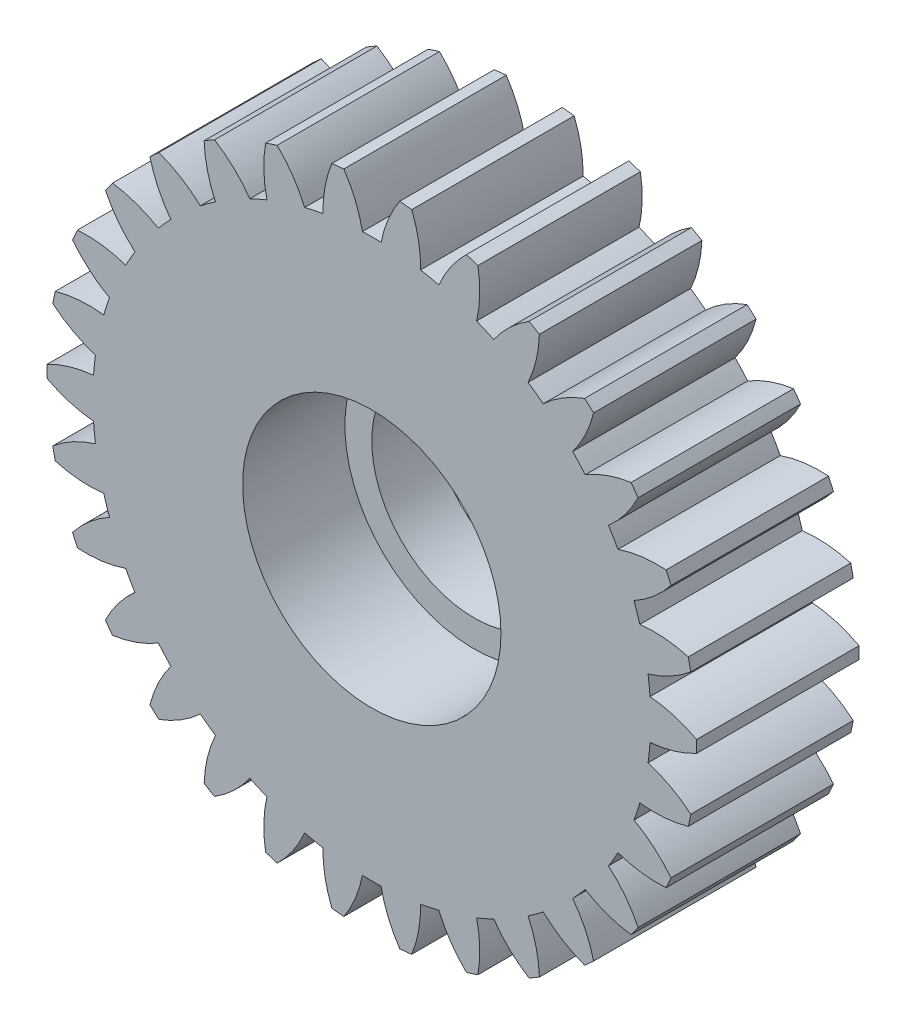
SolidWorks part; units mm, degrees
ref_plane "Front Plane" through (0, 0, 0) normal (0, 0, 1) x (1, 0, 0)
ref_plane "Top Plane" through (0, 0, 0) normal (0, 1, 0) x (1, 0, 0)
ref_plane "Right Plane" through (0, 0, 0) normal (1, 0, 0) x (0, 0, -1)
sketch "Sketch1" plane through (0, 0, 0) normal (0, 0, 1) x (1, 0, 0)
  arc B0 (-12.6978, -0.2355) -> (-10.8753, -0.7756) centre (-10.4606, 3.9688) ccw
  arc B1 (-10.8753, -0.7756) -> (-10.7989, -1.5025) centre (0, 0) ccw
  arc B2 (-10.7989, -1.5025) -> (-12.4693, -2.4097) centre (-9.4069, -6.057) ccw
  arc B3 (-12.4693, -2.4097) -> (-12.3714, -2.8704) centre (0, 0) ccw
  arc B4 (-12.3714, -2.8704) -> (-10.4764, -3.0197) centre (-11.0572, 1.7072) ccw
  arc B5 (-10.4764, -3.0197) -> (-10.2506, -3.7149) centre (0, 0) ccw
  arc B6 (-10.2506, -3.7149) -> (-11.6958, -4.9495) centre (-7.942, -7.8804) ccw
  arc B7 (-11.6958, -4.9495) -> (-11.5042, -5.3798) centre (0, 0) ccw
  arc B8 (-11.5042, -5.3798) -> (-9.6197, -5.1319) centre (-11.1705, -0.629) ccw
  arc B9 (-9.6197, -5.1319) -> (-9.2542, -5.7649) centre (0, 0) ccw
  arc B10 (-9.2542, -5.7649) -> (-10.4112, -7.2731) centre (-6.13, -9.3594) ccw
  arc B11 (-10.4112, -7.2731) -> (-10.1343, -7.6541) centre (0, 0) ccw
  arc B12 (-10.1343, -7.6541) -> (-8.3425, -7.0198) centre (-10.7956, -2.9377) ccw
  arc B13 (-8.3425, -7.0198) -> (-7.8534, -7.563) centre (0, 0) ccw
  arc B14 (-7.8534, -7.563) -> (-8.6715, -9.2787) centre (-4.0501, -10.4294) ccw
  arc B15 (-8.6715, -9.2787) -> (-8.3215, -9.5939) centre (0, 0) ccw
  arc B16 (-8.3215, -9.5939) -> (-6.7006, -8.6009) centre (-9.9489, -5.1181) ccw
  arc B17 (-6.7006, -8.6009) -> (-6.1093, -9.0305) centre (0, 0) ccw
  arc B18 (-6.1093, -9.0305) -> (-6.5529, -10.8789) centre (-1.7932, -11.0436) ccw
  arc B19 (-6.5529, -10.8789) -> (-6.145, -11.1144) centre (0, 0) ccw
  arc B20 (-6.145, -11.1144) -> (-4.766, -9.8061) centre (-8.6674, -7.0747) ccw
  arc B21 (-4.766, -9.8061) -> (-4.0983, -10.1034) centre (0, 0) ccw
  arc B22 (-4.0983, -10.1034) -> (-4.1478, -12.0036) centre (0.5421, -11.1751) ccw
  arc B23 (-4.1478, -12.0036) -> (-3.6999, -12.1491) centre (0, 0) ccw
  arc B24 (-3.6999, -12.1491) -> (-2.623, -10.5827) centre (-7.0071, -8.7222) ccw
  arc B25 (-2.623, -10.5827) -> (-1.9081, -10.7347) centre (0, 0) ccw
  arc B26 (-1.9081, -10.7347) -> (-1.5615, -12.6036) centre (2.8537, -10.8182) ccw
  arc B27 (-1.5615, -12.6036) -> (-1.0931, -12.6529) centre (0, 0) ccw
  arc B28 (-1.0931, -12.6529) -> (-0.3654, -10.8968) centre (-5.0405, -9.9885) ccw
  arc B29 (-0.3654, -10.8968) -> (0.3654, -10.8968) centre (0, 0) ccw
  arc B30 (0.3654, -10.8968) -> (1.0931, -12.6529) centre (5.0405, -9.9885) ccw
  arc B31 (1.0931, -12.6529) -> (1.5615, -12.6036) centre (0, 0) ccw
  arc B32 (1.5615, -12.6036) -> (1.9081, -10.7347) centre (-2.8537, -10.8182) ccw
  arc B33 (1.9081, -10.7347) -> (2.623, -10.5827) centre (0, 0) ccw
  arc B34 (2.623, -10.5827) -> (3.6999, -12.1491) centre (7.0071, -8.7222) ccw
  arc B35 (3.6999, -12.1491) -> (4.1478, -12.0036) centre (0, 0) ccw
  arc B36 (4.1478, -12.0036) -> (4.0983, -10.1034) centre (-0.5421, -11.1751) ccw
  arc B37 (4.0983, -10.1034) -> (4.766, -9.8061) centre (0, 0) ccw
  arc B38 (4.766, -9.8061) -> (6.145, -11.1144) centre (8.6674, -7.0747) ccw
  arc B39 (6.145, -11.1144) -> (6.5529, -10.8789) centre (0, 0) ccw
  arc B40 (6.5529, -10.8789) -> (6.1093, -9.0305) centre (1.7932, -11.0436) ccw
  arc B41 (6.1093, -9.0305) -> (6.7006, -8.6009) centre (0, 0) ccw
  arc B42 (6.7006, -8.6009) -> (8.3215, -9.5939) centre (9.9489, -5.1181) ccw
  arc B43 (8.3215, -9.5939) -> (8.6715, -9.2787) centre (0, 0) ccw
  arc B44 (8.6715, -9.2787) -> (7.8534, -7.563) centre (4.0501, -10.4294) ccw
  arc B45 (7.8534, -7.563) -> (8.3425, -7.0198) centre (0, 0) ccw
  arc B46 (8.3425, -7.0198) -> (10.1343, -7.6541) centre (10.7956, -2.9377) ccw
  arc B47 (10.1343, -7.6541) -> (10.4112, -7.2731) centre (0, 0) ccw
  arc B48 (10.4112, -7.2731) -> (9.2542, -5.7649) centre (6.13, -9.3594) ccw
  arc B49 (9.2542, -5.7649) -> (9.6197, -5.1319) centre (0, 0) ccw
  arc B50 (9.6197, -5.1319) -> (11.5042, -5.3798) centre (11.1705, -0.629) ccw
  arc B51 (11.5042, -5.3798) -> (11.6958, -4.9495) centre (0, 0) ccw
  arc B52 (11.6958, -4.9495) -> (10.2506, -3.7149) centre (7.942, -7.8804) ccw
  arc B53 (10.2506, -3.7149) -> (10.4764, -3.0197) centre (0, 0) ccw
  arc B54 (10.4764, -3.0197) -> (12.3714, -2.8704) centre (11.0572, 1.7072) ccw
  arc B55 (12.3714, -2.8704) -> (12.4693, -2.4097) centre (0, 0) ccw
  arc B56 (12.4693, -2.4097) -> (10.7989, -1.5025) centre (9.4069, -6.057) ccw
  arc B57 (10.7989, -1.5025) -> (10.8753, -0.7756) centre (0, 0) ccw
  arc B58 (10.8753, -0.7756) -> (12.6978, -0.2355) centre (10.4606, 3.9688) ccw
  arc B59 (12.6978, -0.2355) -> (12.6978, 0.2355) centre (0, 0) ccw
  arc B60 (12.6978, 0.2355) -> (10.8753, 0.7756) centre (10.4606, -3.9688) ccw
  arc B61 (10.8753, 0.7756) -> (10.7989, 1.5025) centre (0, 0) ccw
  arc B62 (10.7989, 1.5025) -> (12.4693, 2.4097) centre (9.4069, 6.057) ccw
  arc B63 (12.4693, 2.4097) -> (12.3714, 2.8704) centre (0, 0) ccw
  arc B64 (12.3714, 2.8704) -> (10.4764, 3.0197) centre (11.0572, -1.7072) ccw
  arc B65 (10.4764, 3.0197) -> (10.2506, 3.7149) centre (0, 0) ccw
  arc B66 (10.2506, 3.7149) -> (11.6958, 4.9495) centre (7.942, 7.8804) ccw
  arc B67 (11.6958, 4.9495) -> (11.5042, 5.3798) centre (0, 0) ccw
  arc B68 (11.5042, 5.3798) -> (9.6197, 5.1319) centre (11.1705, 0.629) ccw
  arc B69 (9.6197, 5.1319) -> (9.2542, 5.7649) centre (0, 0) ccw
  arc B70 (9.2542, 5.7649) -> (10.4112, 7.2731) centre (6.13, 9.3594) ccw
  arc B71 (10.4112, 7.2731) -> (10.1343, 7.6541) centre (0, 0) ccw
  arc B72 (10.1343, 7.6541) -> (8.3425, 7.0198) centre (10.7956, 2.9377) ccw
  arc B73 (8.3425, 7.0198) -> (7.8534, 7.563) centre (0, 0) ccw
  arc B74 (7.8534, 7.563) -> (8.6715, 9.2787) centre (4.0501, 10.4294) ccw
  arc B75 (8.6715, 9.2787) -> (8.3215, 9.5939) centre (0, 0) ccw
  arc B76 (8.3215, 9.5939) -> (6.7006, 8.6009) centre (9.9489, 5.1181) ccw
  arc B77 (6.7006, 8.6009) -> (6.1093, 9.0305) centre (0, 0) ccw
  arc B78 (6.1093, 9.0305) -> (6.5529, 10.8789) centre (1.7932, 11.0436) ccw
  arc B79 (6.5529, 10.8789) -> (6.145, 11.1144) centre (0, 0) ccw
  arc B80 (6.145, 11.1144) -> (4.766, 9.8061) centre (8.6674, 7.0747) ccw
  arc B81 (4.766, 9.8061) -> (4.0983, 10.1034) centre (0, 0) ccw
  arc B82 (4.0983, 10.1034) -> (4.1478, 12.0036) centre (-0.5421, 11.1751) ccw
  arc B83 (4.1478, 12.0036) -> (3.6999, 12.1491) centre (0, 0) ccw
  arc B84 (3.6999, 12.1491) -> (2.623, 10.5827) centre (7.0071, 8.7222) ccw
  arc B85 (2.623, 10.5827) -> (1.9081, 10.7347) centre (0, 0) ccw
  arc B86 (1.9081, 10.7347) -> (1.5615, 12.6036) centre (-2.8537, 10.8182) ccw
  arc B87 (1.5615, 12.6036) -> (1.0931, 12.6529) centre (0, 0) ccw
  arc B88 (1.0931, 12.6529) -> (0.3654, 10.8968) centre (5.0405, 9.9885) ccw
  arc B89 (0.3654, 10.8968) -> (-0.3654, 10.8968) centre (0, 0) ccw
  arc B90 (-0.3654, 10.8968) -> (-1.0931, 12.6529) centre (-5.0405, 9.9885) ccw
  arc B91 (-1.0931, 12.6529) -> (-1.5615, 12.6036) centre (0, 0) ccw
  arc B92 (-1.5615, 12.6036) -> (-1.9081, 10.7347) centre (2.8537, 10.8182) ccw
  arc B93 (-1.9081, 10.7347) -> (-2.623, 10.5827) centre (0, 0) ccw
  arc B94 (-2.623, 10.5827) -> (-3.6999, 12.1491) centre (-7.0071, 8.7222) ccw
  arc B95 (-3.6999, 12.1491) -> (-4.1478, 12.0036) centre (0, 0) ccw
  arc B96 (-4.1478, 12.0036) -> (-4.0983, 10.1034) centre (0.5421, 11.1751) ccw
  arc B97 (-4.0983, 10.1034) -> (-4.766, 9.8061) centre (0, 0) ccw
  arc B98 (-4.766, 9.8061) -> (-6.145, 11.1144) centre (-8.6674, 7.0747) ccw
  arc B99 (-6.145, 11.1144) -> (-6.5529, 10.8789) centre (0, 0) ccw
  arc B100 (-6.5529, 10.8789) -> (-6.1093, 9.0305) centre (-1.7932, 11.0436) ccw
  arc B101 (-6.1093, 9.0305) -> (-6.7006, 8.6009) centre (0, 0) ccw
  arc B102 (-6.7006, 8.6009) -> (-8.3215, 9.5939) centre (-9.9489, 5.1181) ccw
  arc B103 (-8.3215, 9.5939) -> (-8.6715, 9.2787) centre (0, 0) ccw
  arc B104 (-8.6715, 9.2787) -> (-7.8534, 7.563) centre (-4.0501, 10.4294) ccw
  arc B105 (-7.8534, 7.563) -> (-8.3425, 7.0198) centre (0, 0) ccw
  arc B106 (-8.3425, 7.0198) -> (-10.1343, 7.6541) centre (-10.7956, 2.9377) ccw
  arc B107 (-10.1343, 7.6541) -> (-10.4112, 7.2731) centre (0, 0) ccw
  arc B108 (-10.4112, 7.2731) -> (-9.2542, 5.7649) centre (-6.13, 9.3594) ccw
  arc B109 (-9.2542, 5.7649) -> (-9.6197, 5.1319) centre (0, 0) ccw
  arc B110 (-9.6197, 5.1319) -> (-11.5042, 5.3798) centre (-11.1705, 0.629) ccw
  arc B111 (-11.5042, 5.3798) -> (-11.6958, 4.9495) centre (0, 0) ccw
  arc B112 (-11.6958, 4.9495) -> (-10.2506, 3.7149) centre (-7.942, 7.8804) ccw
  arc B113 (-10.2506, 3.7149) -> (-10.4764, 3.0197) centre (0, 0) ccw
  arc B114 (-10.4764, 3.0197) -> (-12.3714, 2.8704) centre (-11.0572, -1.7072) ccw
  arc B115 (-12.3714, 2.8704) -> (-12.4693, 2.4097) centre (0, 0) ccw
  arc B116 (-12.4693, 2.4097) -> (-10.7989, 1.5025) centre (-9.4069, 6.057) ccw
  arc B117 (-10.7989, 1.5025) -> (-10.8753, 0.7756) centre (0, 0) ccw
  arc B118 (-10.8753, 0.7756) -> (-12.6978, 0.2355) centre (-10.4606, -3.9688) ccw
  arc B119 (-12.6978, 0.2355) -> (-12.6978, -0.2355) centre (0, 0) ccw
sketch_block_instance "Drive_Gear-1"
sketch_block "Drive_Gear"
extrude "Boss-Extrude1" add sketch "Sketch1" along normal blind 6.35
sketch "Sketch2" plane through (0, 0, 6.35) normal (0, 0, 1) x (1, 0, 0)
  circle A0 centre (0, 0) radius 5.05
  dimension "D1" = 10.1
extrude "Cut-Extrude1" cut sketch "Sketch2" against normal blind 4
sketch "Sketch3" plane through (0, 0, 2.35) normal (0, 0, 1) x (1, 0, 0)
  circle A0 centre (0, 0) radius 4
  dimension "D1" = 8
extrude "Cut-Extrude2" cut sketch "Sketch3" against normal through all contours A0
